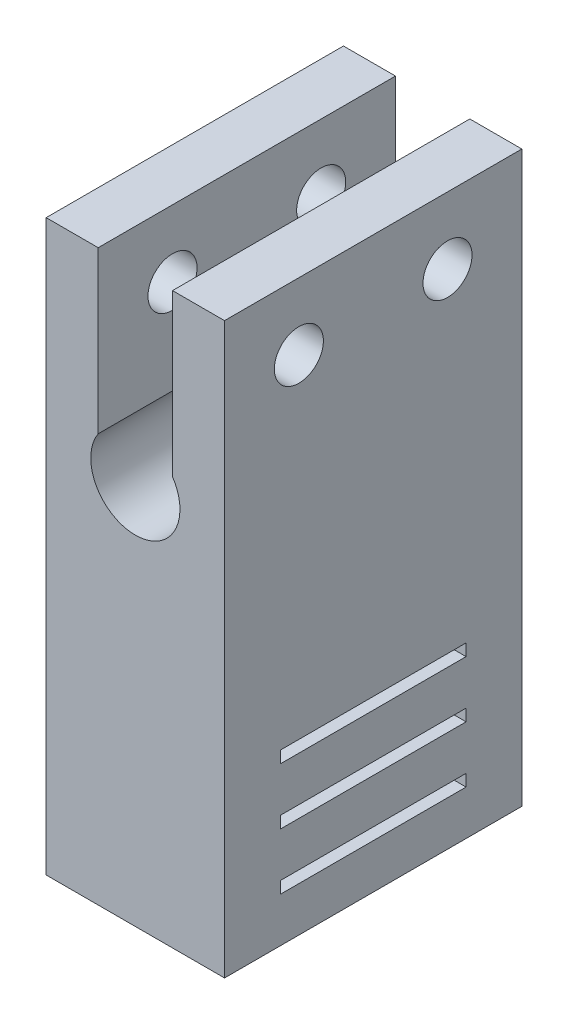
SolidWorks part; units mm, degrees
ref_plane "xy" through (0, 0, 0) normal (0, 0, 1) x (1, 0, 0)
ref_plane "xz" through (0, 0, 0) normal (0, 1, 0) x (1, 0, 0)
ref_plane "yz" through (0, 0, 0) normal (1, 0, 0) x (0, 0, -1)
sketch "Skizze1" plane through (0, 0, 0) normal (1, 0, 0) x (0, 0, -1)
  line L0 (5, 33.8) -> (15, 33.8) construction
  line L1 (0, 0) -> (20, 0)
  line L2 (0, 0) -> (0, 38.3)
  line L3 (0, 38.3) -> (20, 38.3)
  line L4 (20, 0) -> (20, 38.3)
  line L5 (3.75, 3.8) -> (16.25, 3.8)
  line L6 (3.75, 3.8) -> (3.75, 3)
  line L7 (3.75, 3) -> (16.25, 3)
  line L8 (16.25, 3.8) -> (16.25, 3)
  line L9 (3.75, 7.6) -> (16.25, 7.6)
  line L10 (3.75, 7.6) -> (3.75, 6.8)
  line L11 (3.75, 6.8) -> (16.25, 6.8)
  line L12 (16.25, 7.6) -> (16.25, 6.8)
  line L13 (3.75, 10.6) -> (16.25, 10.6)
  line L14 (3.75, 10.6) -> (3.75, 11.4)
  line L15 (3.75, 11.4) -> (16.25, 11.4)
  line L16 (16.25, 10.6) -> (16.25, 11.4)
  line L17 (15, 33.8) -> (10, 33.8) construction
  line L18 (10, 33.8) -> (10, 38.3) construction
  line L19 (0, 25.8) -> (20, 25.8) construction
  line L20 (16.25, 3.8) -> (16.25, 6.8) construction
  line L21 (16.25, 7.6) -> (16.25, 10.6) construction
  circle A2 centre (5, 33.8) radius 1.65
  circle A3 centre (15, 33.8) radius 1.65
  dimension "D2" = 4.5
  dimension "D12" = 3.3
  dimension "D3" = 0.8
  dimension "D4" = 12.5
  dimension "D5" = 3
  dimension "D6" = 3
  dimension "D7" = 3.75
  dimension "D11" = 20
  dimension "D13" = 22
  dimension "D14" = 10
  dimension "D15" = 8
extrude "Aufsatz-Linear austragen1" add sketch "Skizze1" along normal blind 12
sketch "Skizze2" plane through (0, 0, 0) normal (0, 0, 1) x (1, 0, 0)
  line L0 (12, 38.3) -> (0, 38.3) construction
  line L2 (3.5, 38.3) -> (8.5, 38.3)
  line L4 (3.5, 38.3) -> (3.5, 27.4583)
  line L6 (8.5, 38.3) -> (8.5, 27.4583)
  arc A0 (3.5, 27.4583) -> (8.5, 27.4583) centre (6, 25.8) ccw
  point P4 (6, 38.3)
  dimension "D1" = 6
  dimension "D2" = 5
extrude "Schnitt-Linear austragen2" cut sketch "Skizze2" against normal through all
